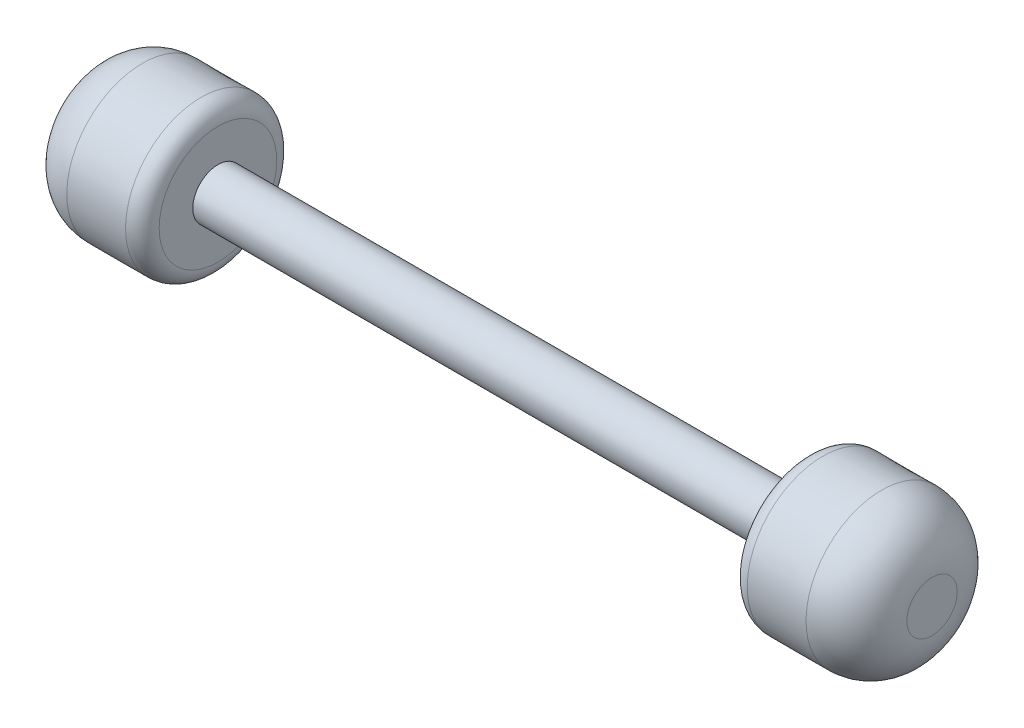
SolidWorks part; units mm, degrees
ref_plane "Front Plane" through (0, 0, 0) normal (0, 0, 1) x (1, 0, 0)
ref_plane "Top Plane" through (0, 0, 0) normal (0, 1, 0) x (1, 0, 0)
ref_plane "Right Plane" through (0, 0, 0) normal (1, 0, 0) x (0, 0, -1)
sketch "Sketch1" plane through (0, 0, 0) normal (0, 0, 1) x (1, 0, 0)
  line L1 (-35, -1.5) -> (35, -1.5)
  line L2 (-35, -1.5) -> (-35, 1.5)
  line L3 (-35, 1.5) -> (35, 1.5)
  line L4 (35, -1.5) -> (35, 1.5)
  line L5 (-35, -1.5) -> (35, 1.5) construction
  line L6 (-35, 1.5) -> (35, -1.5) construction
  point P0 (0, 0)
  dimension "D1" = 70
  dimension "D2" = 3
revolve "Revolve1" add sketch "Sketch1" angle 360 about L3
sketch "Sketch2" plane through (0, 0, 0) normal (0, 0, 1) x (1, 0, 0)
  line L1 (-37, -7.5541) -> (-44, -7.5541)
  line L3 (-44, 10.4459) -> (-37, 10.4459)
  line L4 (-37, 10.4459) -> (-37, -7.5541)
  line L7 (-35, 8.4459) -> (-35, -5.5541)
  line L9 (-50, 4.4459) -> (-50, -1.5561)
  line L10 (-50, 1.4449) -> (-35, 1.4459) construction
  line L11 (-44, 10.4459) -> (-44, -7.5541)
  arc A0 (-35, -5.5541) -> (-37, -7.5541) centre (-37, -5.5541) cw
  arc A1 (-35, 8.4459) -> (-37, 10.4459) centre (-37, 8.4459) ccw
  arc A2 (-44, -7.5541) -> (-50, -1.5561) centre (-44, -1.5541) cw
  arc A3 (-44, 10.4459) -> (-50, 4.4459) centre (-44, 4.4459) ccw
  dimension "D2" = 2
  dimension "D4" = 6
  dimension "D5" = 6
  dimension "D1" = 18
  dimension "D3" = 7
revolve "Revolve2" add sketch "Sketch2" angle 360 about L10
ref_plane "Plane1" through (0, 0, 0) normal (1, 0, 0) x (0, 0, -1)
mirror "Mirror1" about plane through (0, 0, 0) normal (1, 0, 0) of "Revolve2"
